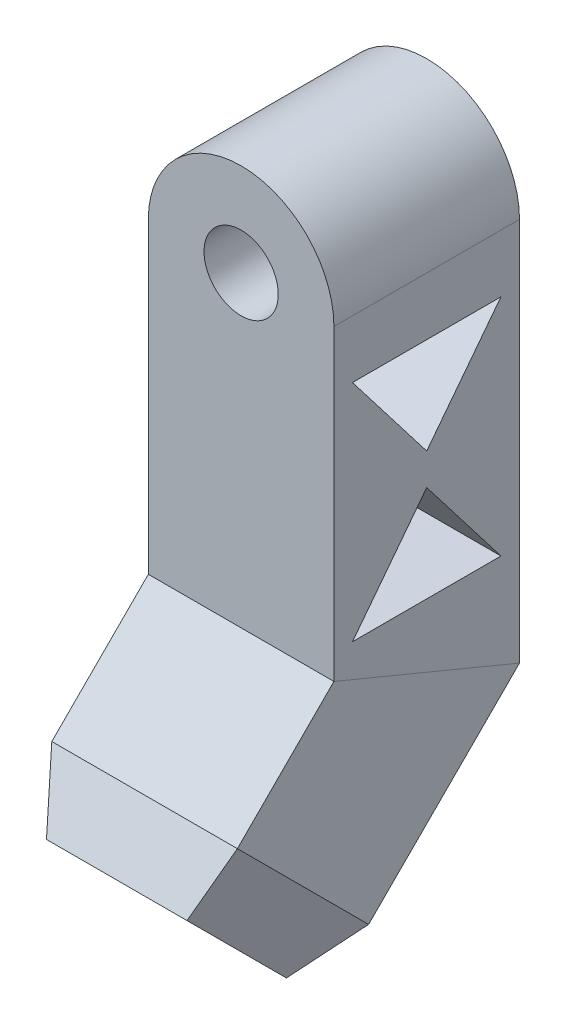
SolidWorks part; units mm, degrees
ref_plane "Front Plane" through (0, 0, 0) normal (0, 0, 1) x (1, 0, 0)
ref_plane "Top Plane" through (0, 0, 0) normal (0, 1, 0) x (1, 0, 0)
ref_plane "Right Plane" through (0, 0, 0) normal (1, 0, 0) x (0, 0, -1)
ref_plane "Plane2" through (0, 96.393, 0) normal (0, 1, 0) x (1, 0, 0)
sketch "Sketch10" plane through (0, 0, 0) normal (1, 0, 0) x (0, 0, -1)
  line L0 (0, 96.393) -> (0, 25.4)
  line L1 (55, 96.393) -> (-55, 96.393) construction
  line L2 (0, 25.4) -> (-25.4, 0)
  line L3 (55, 0) -> (-55, 0) construction
  dimension "D1" = 70.993
  dimension "D2" = 135
sketch "Sketch11" plane through (0, 96.393, 0) normal (0, 1, 0) x (1, 0, 0)
  line L1 (-19.05, -19.05) -> (19.05, -19.05)
  line L2 (-19.05, -19.05) -> (-19.05, 19.05)
  line L3 (-19.05, 19.05) -> (19.05, 19.05)
  line L4 (19.05, -19.05) -> (19.05, 19.05)
  line L5 (-19.05, -19.05) -> (19.05, 19.05) construction
  line L6 (-19.05, 19.05) -> (19.05, -19.05) construction
  point P0 (0, 0)
  dimension "D1" = 38.1
sweep "Sweep1" add profiles "Sketch11" path "Sketch10"
sketch "Sketch12" plane through (0, -12.7, 12.7) normal (0, -0.7071, 0.7071) x (1, 0, 0)
  line L8 (19.05, -1.0895) -> (19.05, 37.0105)
  line L9 (19.05, 37.0105) -> (-19.05, 37.0105)
  line L10 (-19.05, 37.0105) -> (-19.05, -1.0895)
  line L11 (-19.05, -1.0895) -> (19.05, -1.0895)
  line L12 (19.05, -1.0895) -> (19.05, 37.0105)
  line L13 (19.05, 37.0105) -> (-19.05, 37.0105)
  line L14 (-19.05, 37.0105) -> (-19.05, -1.0895)
  line L15 (-19.05, -1.0895) -> (19.05, -1.0895)
  dimension "D1" = 0
extrude "Boss-Extrude5" add sketch "Sketch12" along normal blind 12.7 draft 20
sketch "Sketch13" plane through (0, 0, -19.05) normal (0, 0, -1) x (-1, 0, 0)
  line L0 (55, 96.393) -> (-55, 96.393) construction
  line L1 (0, 55) -> (0, -55) construction
  line L2 (-19.05, 96.393) -> (19.05, 96.393)
  arc A0 (19.05, 96.393) -> (-19.05, 96.393) centre (0, 96.393) ccw
  dimension "D1" = 38.1
extrude "Boss-Extrude6" add sketch "Sketch13" against normal up to surface (38.1 mm away) up to face at (0, 64.8419, 19.05)
sketch "Sketch14" plane through (0, 0, 19.05) normal (0, 0, 1) x (1, 0, 0)
  circle A0 centre (0, 96.393) radius 7.62
  arc A1 (19.05, 96.393) -> (-19.05, 96.393) centre (0, 96.393) ccw construction
  dimension "D1" = 15.24
extrude "Cut-Extrude2" cut sketch "Sketch14" against normal blind 38.1
sketch "Sketch15" plane through (0, -21.6803, 21.6803) normal (0, -0.7071, 0.7071) x (1, 0, 0)
  line L0 (0, -34.9977) -> (0, 34.9977) construction
  line L4 (-14.4276, 32.3881) -> (-14.4276, 3.5329) construction
  line L5 (-14.4276, 3.5329) -> (14.4276, 3.5329) construction
  line L8 (0, 32.3881) -> (0, 3.5329) construction
  line L9 (14.4276, 32.3881) -> (-14.4276, 32.3881) construction
  circle A0 centre (0, 17.9605) radius 12.065
  point P12 (-14.4276, 17.9605)
  dimension "D1" = 24.13
extrude "Cut-Extrude3" cut sketch "Sketch15" against normal blind 12.7
sketch "Sketch16" plane through (-19.05, 0, 0) normal (-1, 0, 0) x (0, 0, 1)
  line L0 (-15.24, 38.4454) -> (0, 58.2328)
  line L2 (0, 58.2328) -> (15.24, 38.4454)
  line L3 (-19.05, 61.4842) -> (19.05, 61.4842) construction
  line L10 (-15.24, 38.4454) -> (15.24, 38.4454)
  line L13 (-19.05, 96.393) -> (-19.05, 17.5092) construction
  line L14 (19.05, 96.393) -> (19.05, 33.2908) construction
  line L15 (-15.24, 84.5229) -> (15.24, 84.5229)
  line L16 (0, 64.7355) -> (15.24, 84.5229)
  line L17 (-15.24, 84.5229) -> (0, 64.7355)
  dimension "D1" = 52.397
  dimension "D2" = 52.397
  dimension "D3" = 58.2328
  dimension "D4" = 38.4454
  dimension "D5" = 30.48
  dimension "D6" = 38.1
  dimension "D7" = 61.4842
  dimension "D9" = 38.4454
extrude "Cut-Extrude4" cut sketch "Sketch16" against normal blind 38.1
